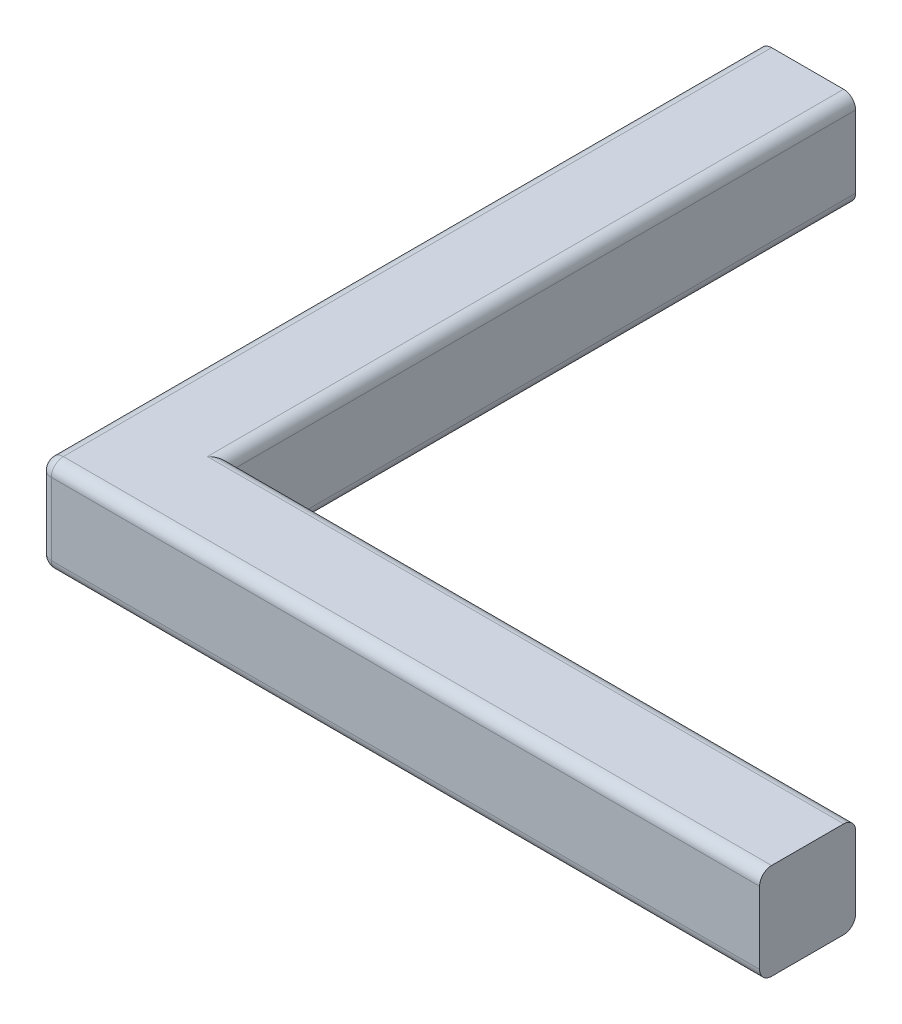
SolidWorks part; units mm, degrees
ref_plane "Front Plane" through (0, 0, 0) normal (0, 0, 1) x (1, 0, 0)
ref_plane "Top Plane" through (0, 0, 0) normal (0, 1, 0) x (1, 0, 0)
ref_plane "Right Plane" through (0, 0, 0) normal (1, 0, 0) x (0, 0, -1)
sketch "Sketch1" plane through (0, 0, 0) normal (0, 1, 0) x (1, 0, 0)
  line L1 (0, 0) -> (300, 0)
  line L2 (0, 0) -> (0, 40)
  line L3 (40, 40) -> (300, 40)
  line L4 (300, 0) -> (300, 40)
  line L6 (0, 40) -> (0, 300)
  line L7 (0, 300) -> (40, 300)
  line L8 (40, 40) -> (40, 300)
  dimension "D1" = 40
  dimension "D2" = 40
  dimension "D3" = 300
  dimension "D4" = 260
  dimension "D5" = 40
extrude "Boss-Extrude1" add sketch "Sketch1" along normal blind 40
fillet "Fillet1" radius 5 1 edges at (150, 40, 0)
fillet "Fillet2" radius 5 4 edges at (150, 0, 0) (40, 0, -170) (40, 40, -170) (170, 40, -40)
fillet "Fillet3" radius 5 6 edges at (0, 1.4645, -1.4645) (0, 20, 0) (0, 38.5355, -1.4645) (167.5, 0, -40) (0, 0, -152.5) (0, 40, -152.5)
